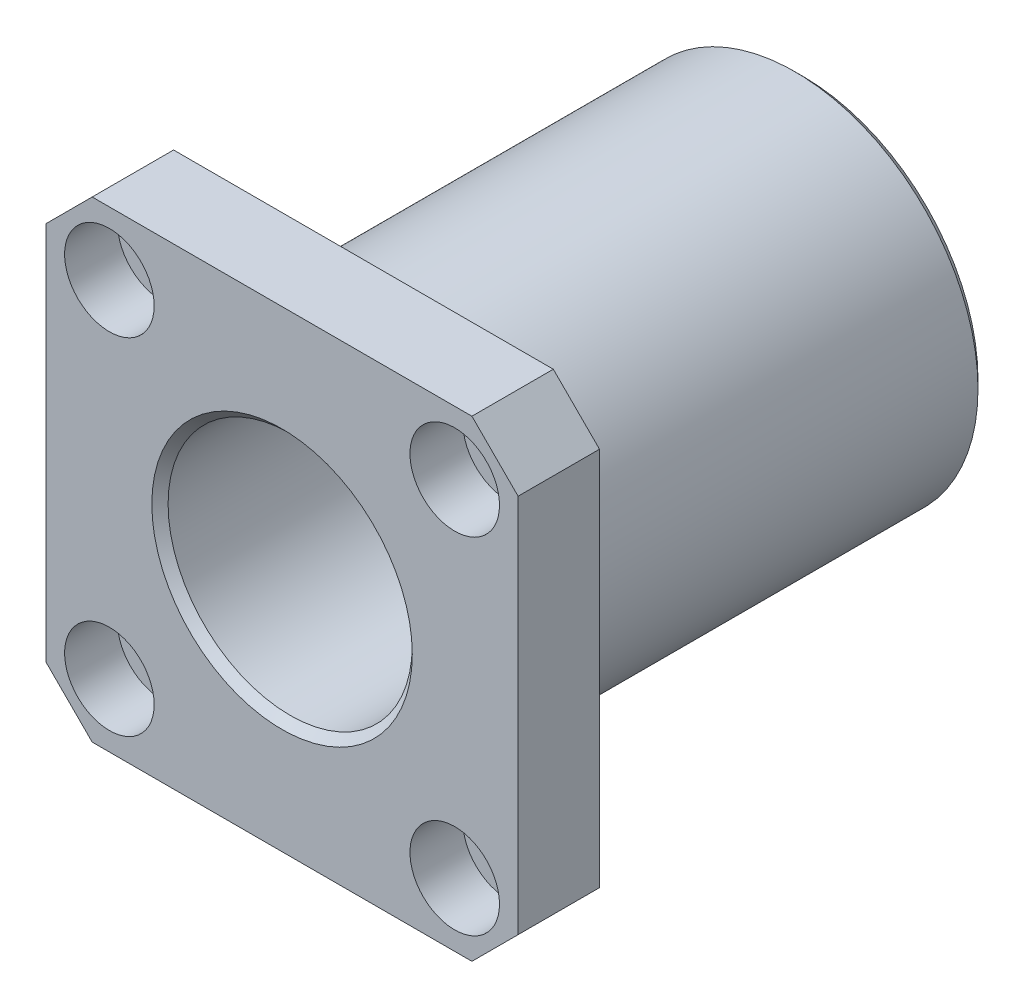
SolidWorks part; units mm, degrees
ref_plane "Front Plane" through (0, 0, 0) normal (0, 0, 1) x (1, 0, 0)
ref_plane "Top Plane" through (0, 0, 0) normal (0, 1, 0) x (1, 0, 0)
ref_plane "Right Plane" through (0, 0, 0) normal (1, 0, 0) x (0, 0, -1)
sketch "Sketch1" plane through (0, 0, 0) normal (0, 0, 1) x (1, 0, 0)
  circle A0 centre (0, 0) radius 22.5
  dimension "D1" = 45
extrude "Boss-Extrude1" add sketch "Sketch1" along normal blind 64
sketch "Sketch2" plane through (0, 0, 64) normal (0, 0, 1) x (1, 0, 0)
  line L1 (-29, -29) -> (29, -29)
  line L2 (-29, -29) -> (-29, 29)
  line L3 (-29, 29) -> (29, 29)
  line L4 (29, -29) -> (29, 29)
  line L5 (-29, -29) -> (29, 29) construction
  line L6 (-29, 29) -> (29, -29) construction
  point P0 (0, 0)
  dimension "D1" = 58
extrude "Boss-Extrude2" add sketch "Sketch2" against normal blind 10
sketch "Sketch4" plane through (0, 0, 64) normal (0, 0, 1) x (1, 0, 0)
  line L0 (0, 29) -> (0, -29) construction
  line L1 (29, 29) -> (-29, 29) construction
  line L2 (-29, -29) -> (29, -29) construction
  line L3 (-29, 29) -> (-29, 23.3259)
  line L4 (-29, 29) -> (-29, -29) construction
  line L5 (-29, 23.3259) -> (-23.3259, 29)
  line L6 (-23.3259, 29) -> (-29, 29)
  line L7 (23.3259, 29) -> (29, 29)
  line L8 (29, 23.3259) -> (23.3259, 29)
  line L9 (29, 29) -> (29, 23.3259)
  line L10 (-29, 0) -> (29, 0) construction
  line L11 (29, -29) -> (29, 29) construction
  line L12 (29, -29) -> (29, -23.3259)
  line L13 (29, -23.3259) -> (23.3259, -29)
  line L14 (23.3259, -29) -> (29, -29)
  line L15 (-23.3259, -29) -> (-29, -29)
  line L16 (-29, -23.3259) -> (-23.3259, -29)
  line L17 (-29, -29) -> (-29, -23.3259)
  dimension "D1" = 74
extrude "Cut-Extrude1" cut sketch "Sketch4" against normal through all
sketch "Sketch5" plane through (0, 0, 64) normal (0, 0, 1) x (1, 0, 0)
  line L0 (0, 0) -> (-26.163, 26.163) construction
  line L1 (-29, 23.3259) -> (-23.3259, 29) construction
  circle A0 centre (0, 0) radius 30 construction
  point P6 (-21.2132, 21.2132)
  point P10 (21.2132, 21.2132)
  point P11 (21.2132, -21.2132)
  point P12 (-21.2132, -21.2132)
  point P13 (0, 0)
  dimension "D1" = 60
  dimension "D2" = 4
hole_wizard "CBORE for M6 Hex Socket Head Cap Screw1" positions "Sketch6" profile "Sketch7" counterbore size "M6" standard "ISO"
sketch "Sketch6" plane through (0, 0, 64) normal (0, 0, 1) x (1, 0, 0)
  point P0 (-21.2132, 21.2132)
  point P3 (21.2132, 21.2132)
  point P6 (21.2132, -21.2132)
  point P9 (-21.2132, -21.2132)
sketch "Sketch7" plane through (-21.2132, 21.2132, 64) normal (1, 0, 0) x (0, -1, 0)
  line L0 (0, 0) -> (0, 23.9828)
  line L1 (0, 23.9828) -> (3.3, 22)
  line L2 (3.3, 22) -> (3.3, 6.5)
  line L3 (3.3, 6.5) -> (5.5, 6.5)
  line L4 (5.5, 6.5) -> (5.5, 0)
  line L5 (5.5, 0) -> (0, 0)
  line L10 (0, 23.9828) -> (-3.3, 22) construction
  line L11 (0, -6.35) -> (0, 107.95) construction
  dimension "Hole Dia." = 6.6
  dimension "Hole Depth" = 22
  dimension "C'Bore Dia." = 11
  dimension "C'Bore Depth" = 6.5
  dimension "Drill Angle" = 118
sketch "Sketch8" plane through (0, 0, 64) normal (0, 0, 1) x (1, 0, 0)
  circle A0 centre (0, 0) radius 15
  dimension "D1" = 30
extrude "Cut-Extrude2" cut sketch "Sketch8" against normal through all
chamfer "Chamfer1" distance 1 angle 45 2 edges at (22.5, 0, 0) (15, 0, 64)
